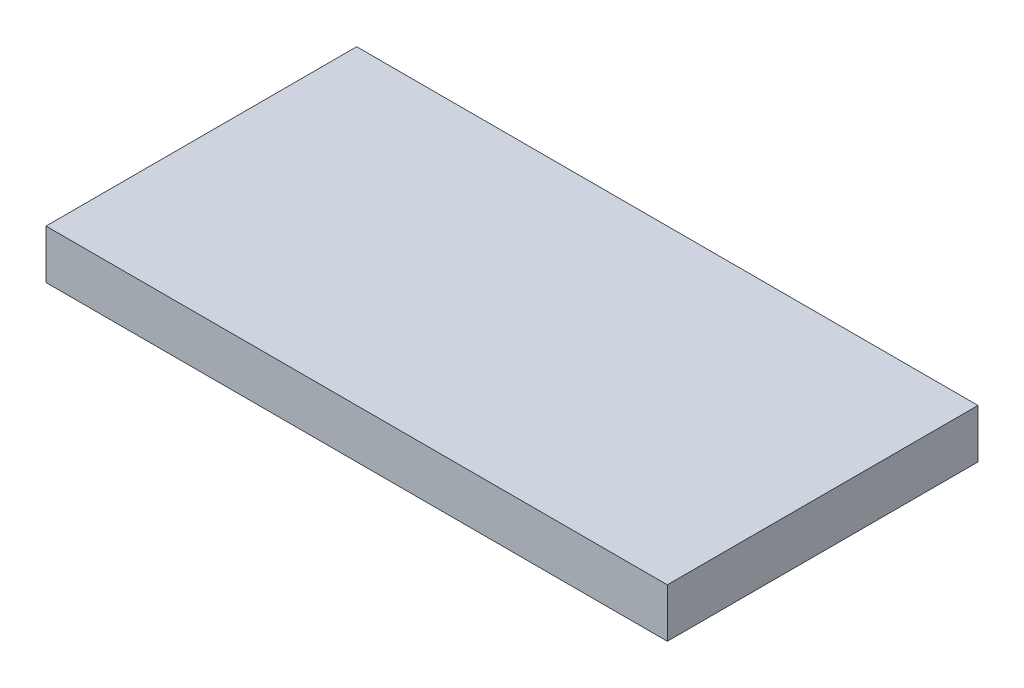
SolidWorks part; units mm, degrees
ref_plane "Front" through (0, 0, 0) normal (0, 0, 1) x (1, 0, 0)
ref_plane "Top" through (0, 0, 0) normal (0, 1, 0) x (1, 0, 0)
ref_plane "Right" through (0, 0, 0) normal (1, 0, 0) x (0, 0, -1)
sketch "草图1" plane through (0, 0, 0) normal (0, 1, 0) x (1, 0, 0)
  line L1 (0, 0) -> (50.8, 0)
  line L2 (0, 0) -> (0, -25.4)
  line L3 (0, -25.4) -> (50.8, -25.4)
  line L4 (50.8, 0) -> (50.8, -25.4)
  dimension "D1" = 50.8
  dimension "D2" = 25.4
extrude "凸台-拉伸1" add sketch "草图1" along normal blind 4
